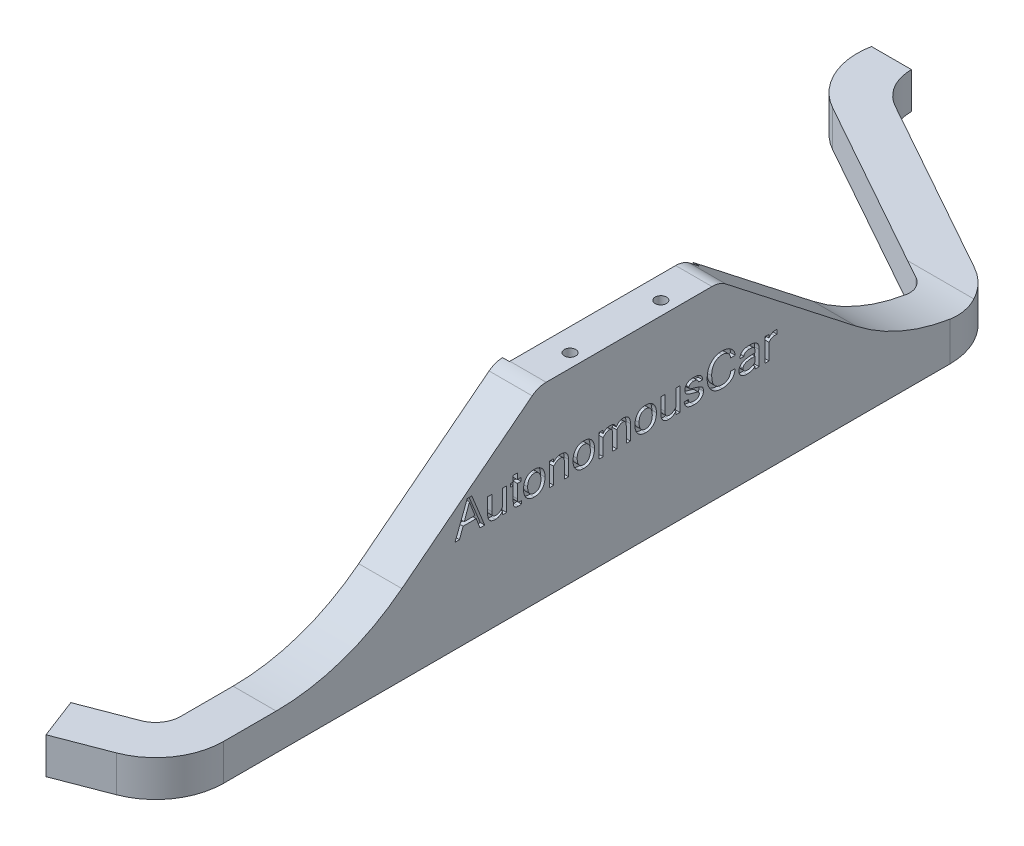
SolidWorks part; units mm, degrees
material "PET"
ref_plane "Plan de face" through (0, 0, 0) normal (0, 0, 1) x (1, 0, 0)
ref_plane "Plan de dessus" through (0, 0, 0) normal (0, 1, 0) x (1, 0, 0)
ref_plane "Plan de droite" through (0, 0, 0) normal (1, 0, 0) x (0, 0, -1)
sketch "Esquisse1" plane through (0, 0, 0) normal (0, 1, 0) x (1, 0, 0)
  line L0 (50.7636, -98.741) -> (61.9667, -94.4409)
  line L1 (65.5, -89.3) -> (65.5, 70.7)
  line L2 (62.6824, 75.5015) -> (21.1873, 98.6833)
  line L3 (54.1678, -107.6101) -> (50.7636, -98.741)
  line L4 (67.3157, 83.795) -> (27.7151, 105.9185)
  line L5 (75, -89.3) -> (75, 70.7)
  line L6 (13.7802, 114.6485) -> (22.5922, 114.6485)
  line L7 (54.1678, -107.6101) -> (65.3709, -103.31)
  line L8 (27.6229, 105.97) -> (67.3157, 83.795) construction
  line L9 (11.8444, -113.6793) -> (61.9667, -94.4409) construction
  line L10 (15.2486, -122.5484) -> (65.3709, -103.31) construction
  arc A0 (61.9667, -94.4409) -> (65.5, -89.3) centre (59.9934, -89.3) ccw
  arc A1 (65.5, 70.7) -> (62.6824, 75.5015) centre (60, 70.7) ccw
  arc A2 (21.1873, 98.6833) -> (13.7802, 114.6485) centre (28.503, 111.7784) cw
  arc A3 (75, 70.7) -> (67.3157, 83.795) centre (60, 70.7) ccw construction
  arc A4 (75, 70.7) -> (67.3157, 83.795) centre (60, 70.7) ccw
  arc A5 (65.3709, -103.31) -> (75, -89.3) centre (59.9934, -89.3) ccw
  arc A6 (65.3709, -103.31) -> (75, -89.3) centre (59.9934, -89.3) ccw construction
  arc A7 (22.2903, 125.7447) -> (21.1873, 98.6833) centre (37.3736, 111.5768) ccw construction
  arc A8 (29.2146, 119.2406) -> (27.7151, 105.9185) centre (37.3736, 111.5768) ccw construction
  arc A9 (22.5922, 114.6485) -> (27.7151, 105.9185) centre (32.5922, 114.6485) ccw
  dimension "D2" = 12
  dimension "D3" = 15
  dimension "D5" = 20
  dimension "D6" = 17
  dimension "D7" = 14.01
  dimension "D8" = 160
  dimension "D1" = 9.5
extrude "Boss.-Extru.2" add sketch "Esquisse1" along normal blind 41
sketch "Esquisse2" plane through (75, 0, 0) normal (1, 0, 0) x (0, 0, -1)
  line L0 (-107.6101, 8) -> (-77.73, 8)
  line L1 (-107.6101, 41) -> (-107.6101, 0) construction
  line L2 (-21.3226, 39.9416) -> (-50.0428, 17.5258)
  line L3 (-89.3, 41) -> (70.7, 41) construction
  line L4 (-107.6101, 8) -> (-107.6101, 51.492)
  line L6 (-107.6101, 51.492) -> (114.6485, 51.492)
  line L7 (114.6485, 51.492) -> (114.6485, 8)
  line L8 (114.6485, 41) -> (114.6485, 0) construction
  line L9 (114.6485, 8) -> (77.7635, 8)
  line L10 (21.3561, 39.9416) -> (50.0763, 17.5258)
  line L11 (-18.2462, 41) -> (18.2797, 41)
  line L12 (83.795, 0) -> (105.9185, 0) construction
  arc A0 (-21.3226, 39.9416) -> (-18.2462, 41) centre (-18.2462, 36) cw
  arc A1 (21.3561, 39.9416) -> (18.2797, 41) centre (18.2797, 36) ccw
  arc A2 (50.0763, 17.5258) -> (77.7635, 8) centre (77.7635, 53) ccw
  arc A3 (-77.73, 8) -> (-50.0428, 17.5258) centre (-77.73, 53) ccw
  point P18 (-19.9665, 41)
  point P21 (20, 41)
  dimension "D1" = 5
  dimension "D2" = 45
  dimension "D3" = 8
extrude "Enlèv. mat.-Extru.1" cut sketch "Esquisse2" against normal up to next
sketch "Esquisse3" plane through (0, 0, 0) normal (0, -1, 0) x (1, 0, 0)
  line L0 (26.6422, -101.0785) -> (64.9998, -79.6495) construction
  line L1 (67.3157, -83.795) -> (27.7151, -105.9185) construction
  line L2 (50.7636, 98.741) -> (54.1678, 107.6101) construction
  line L3 (54.1678, 107.6101) -> (65.3709, 103.31) construction
  line L4 (70.25, 89.3001) -> (70.2514, -70.6999) construction
  line L5 (72, 89.3001) -> (72, -70.6999) construction
  line L6 (75, 89.3) -> (75, -70.7) construction
  line L7 (22.5922, -114.6485) -> (13.7802, -114.6485) construction
  line L19 (52.4657, 103.1755) -> (63.6688, 98.8754) construction
  circle A0 centre (72, 11.0015) radius 1.25
  arc A1 (75, 89.3) -> (65.3709, 103.31) centre (59.9934, 89.3) ccw construction
  arc A2 (64.9998, -79.6495) -> (70.2514, -70.6999) centre (60, -70.7) ccw construction
  arc A3 (67.3157, -83.795) -> (75, -70.7) centre (60, -70.7) ccw construction
  circle A4 centre (72, -39.0785) radius 1.25
  circle A5 centre (63.03, 98.9215) radius 1.25
  circle A8 centre (65.8488, -79.1752) radius 1.25
  arc A12 (70.25, 89.3001) -> (63.6688, 98.8754) centre (59.9934, 89.3) ccw construction
  circle A13 centre (26.6422, -101.0785) radius 1.25
  circle A15 centre (72, 61.0815) radius 1.25
  dimension "D2" = 2.5
  dimension "D3" = 4.05
  dimension "D1" = 13.57
  dimension "D4" = 44.91
  dimension "D5" = 3
  dimension "D6" = 75.57
  dimension "D7" = 50.08
  dimension "D8" = 50.08
  dimension "D9" = 8.97
  dimension "D10" = 37.84
extrude "Enlèv. mat.-Extru.2" cut sketch "Esquisse3" against normal blind 5
sketch "Esquisse5" plane through (0, 0, 0) normal (0, -1, 0) x (1, 0, 0)
  line L0 (65.5, -70.7) -> (65.5, 89.3) construction
  line L1 (65.5, 18.3515) -> (67, 18.3515)
  line L2 (65.5, 18.3515) -> (65.5, -23.6485)
  line L3 (65.5, -23.6485) -> (67, -23.6485)
  line L4 (67, 18.3515) -> (67, -23.6485)
  line L5 (22.5922, -114.6485) -> (13.7802, -114.6485) construction
  dimension "D1" = 42
  dimension "D2" = 91
  dimension "D3" = 1.5
extrude "Enlèv. mat.-Extru.4" cut sketch "Esquisse5" against normal up to surface (41 mm away) up to face at (70.25, 41, -0.0168)
sketch "Esquisse4" plane through (0, 41, 0) normal (0, 1, 0) x (1, 0, 0)
  line L1 (72, 18.2797) -> (72, -18.2462) construction
  line L5 (67, 0.0168) -> (75, 0.0168) construction
  line L6 (67, 18.2797) -> (67, -18.2462) construction
  line L7 (75, -18.2462) -> (75, 18.2797) construction
  line L8 (67, -18.2462) -> (75, -18.2462) construction
  line L9 (67, 18.2797) -> (75, 18.2797) construction
  circle A0 centre (72, 10.0168) radius 1.25
  circle A1 centre (72, -9.9832) radius 1.25
  dimension "D1" = 2.5
  dimension "D2" = 3
  dimension "D3" = 20
  dimension "D4" = 10
extrude "Enlèv. mat.-Extru.3" cut sketch "Esquisse4" against normal blind 5
sketch "Esquisse6" plane through (75, 0, 0) normal (1, 0, 0) x (0, 0, -1)
  line L0 (0, 0) -> (0.0168, 41) construction
  line L1 (-18.2462, 41) -> (18.2797, 41) construction
  line L2 (-46.2321, 20.5) -> (46.2656, 20.5) construction
  line L3 (-50.0428, 17.5258) -> (-21.3226, 39.9416) construction
  line L4 (21.3561, 39.9416) -> (50.0763, 17.5258) construction
  point P11 (0.0084, 20.5)
sketch "Esquisse7" plane through (75, 0, 0) normal (1, 0, 0) x (0, 0, -1)
  text T0 "   AutonomousCar" font "Microsoft Sans Serif" height 7
extrude "Enlèv. mat.-Extru.5" cut sketch "Esquisse7" against normal blind 1
